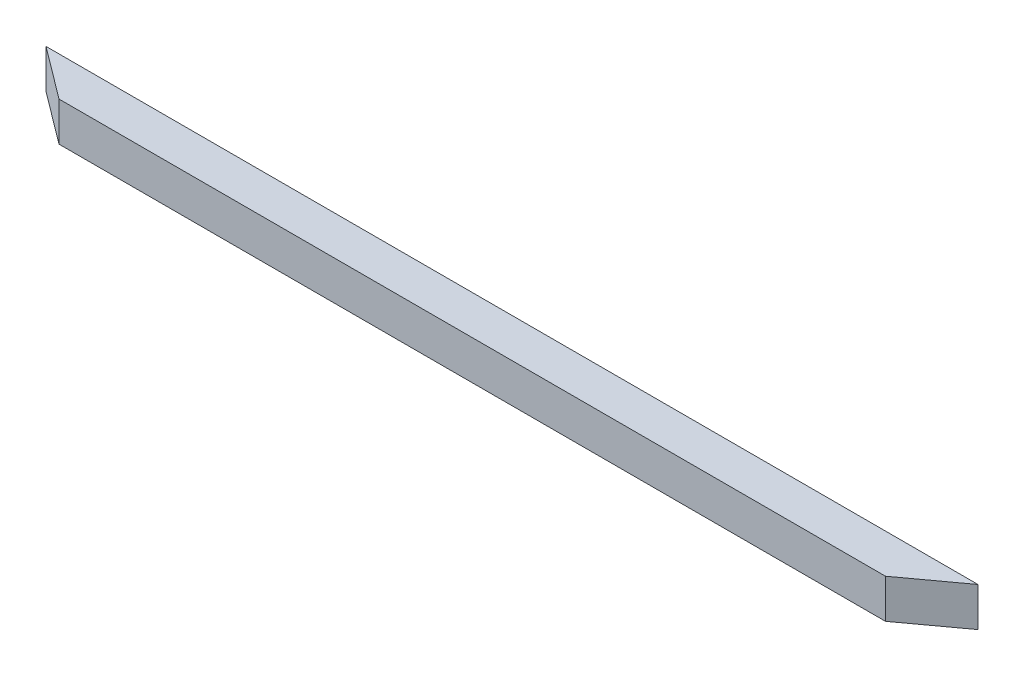
SolidWorks part; units mm, degrees
ref_plane "Front Plane" through (0, 0, 0) normal (0, 0, 1) x (1, 0, 0)
ref_plane "Top Plane" through (0, 0, 0) normal (0, 1, 0) x (1, 0, 0)
ref_plane "Right Plane" through (0, 0, 0) normal (1, 0, 0) x (0, 0, -1)
sketch "Sketch2" plane through (0, 0, 0) normal (0, 1, 0) x (1, 0, 0)
  line L0 (302.768, 12.7) -> (268.0469, -12.7)
  line L1 (-268.9041, -12.7) -> (268.0469, -12.7)
  line L3 (-302.768, 12.7) -> (302.768, 12.7)
  line L5 (-270.6976, -11.3548) -> (302.768, 12.7) construction
  line L6 (-302.768, 12.7) -> (269.9298, -11.3226) construction
  line L7 (-302.768, 12.7) -> (-268.9041, -12.7)
  point P0 (0, 0)
  point P9 (268.0469, -12.7)
  point P10 (-268.9041, -12.7)
  dimension "D1" = 605.536
extrude "Boss-Extrude1" add sketch "Sketch2" along normal blind 25.4
